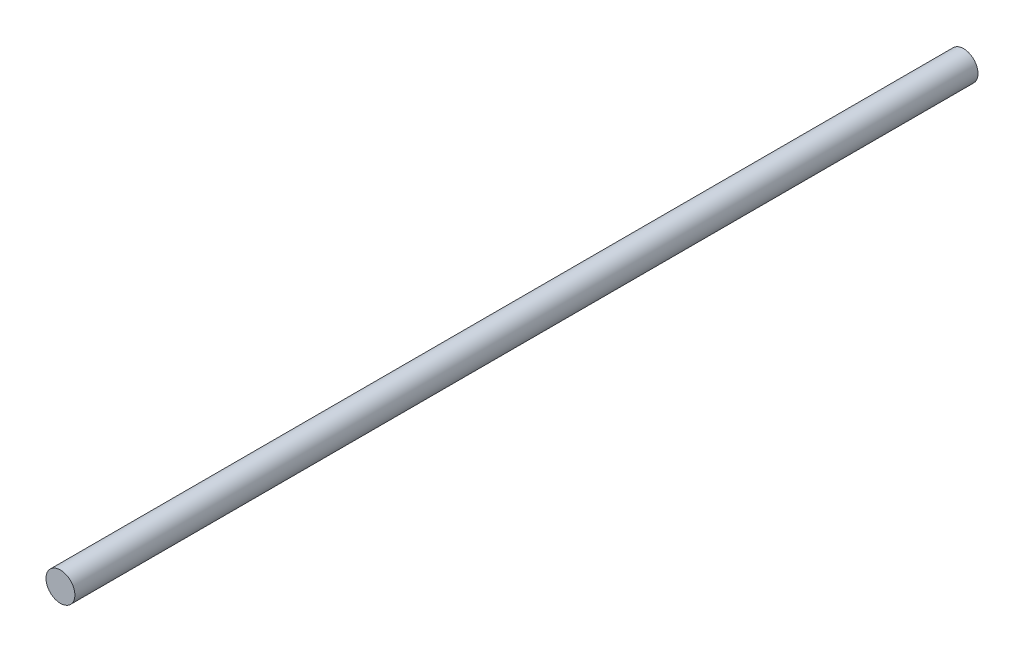
SolidWorks part; units mm, degrees
material "AISI 1020 Steel, Cold Rolled"
ref_plane "Front Plane" through (0, 0, 0) normal (0, 0, 1) x (1, 0, 0)
ref_plane "Top Plane" through (0, 0, 0) normal (0, 1, 0) x (1, 0, 0)
ref_plane "Right Plane" through (0, 0, 0) normal (1, 0, 0) x (0, 0, -1)
sketch "Sketch1" plane through (0, 0, 0) normal (0, 0, 1) x (1, 0, 0)
  circle A0 centre (0, 0) radius 8
  dimension "D1" = 16
extrude "Boss-Extrude1" add sketch "Sketch1" along normal blind 500
ref_plane "Плоскость1" through (0, 0, 0) normal (1, 0, 0) x (0, 0, -1)
equation "\"SBR16.Length.X\"= 600мм"
equation "\"SBR16.Length.Y\"= 500мм"
equation "\"SBR16.Length.Z\"= 250мм"
equation "\"D1@Boss-Extrude1\"= \"SBR16.Length.Y\""
